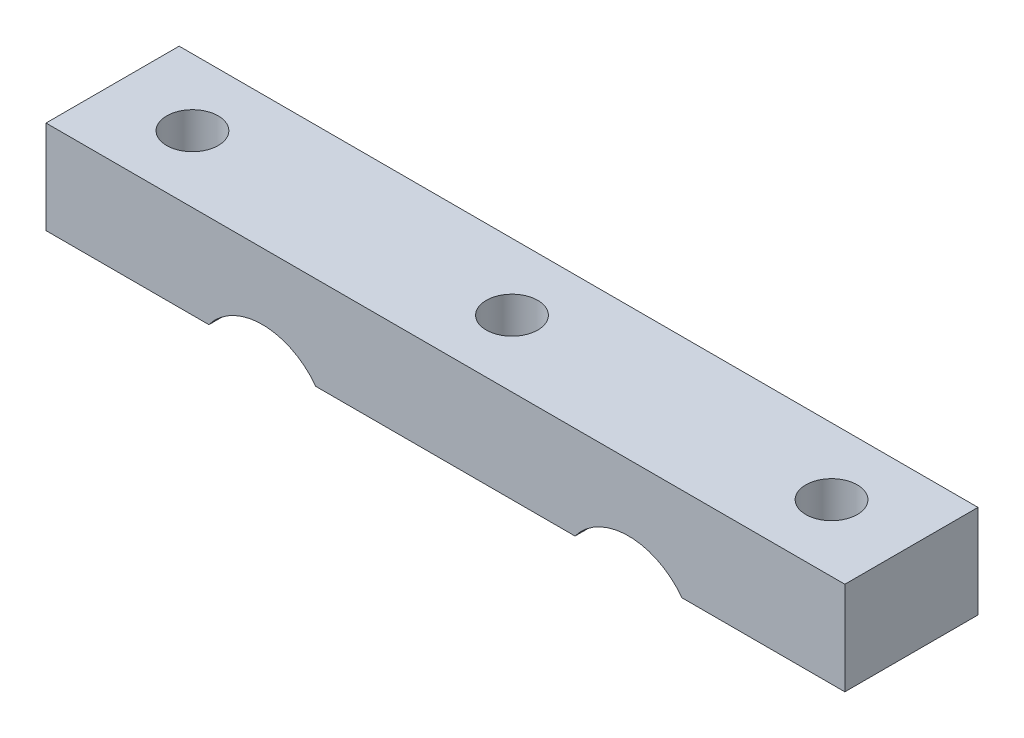
SolidWorks part; units mm, degrees
material "6061-T6 (SS)"
ref_plane "Front Plane" through (0, 0, 0) normal (0, 0, 1) x (1, 0, 0)
ref_plane "Top Plane" through (0, 0, 0) normal (0, 1, 0) x (1, 0, 0)
ref_plane "Right Plane" through (0, 0, 0) normal (1, 0, 0) x (0, 0, -1)
sketch "Sketch1" plane through (0, 0, 0) normal (0, 0, 1) x (1, 0, 0)
  line L0 (-38.1, 17.145) -> (-38.1, 24.7142) construction
  line L3 (-38.1, 17.145) -> (-22.5615, 17.145) construction
  line L5 (38.1, 33.6042) -> (38.1, 24.7142)
  line L6 (22.5615, 24.7142) -> (38.1, 24.7142)
  line L7 (-38.1, 24.7142) -> (-22.5615, 24.7142)
  line L8 (-38.1, 24.7142) -> (-38.1, 33.6042)
  line L9 (-38.1, 33.6042) -> (38.1, 33.6042)
  line L10 (-38.1, 20.9296) -> (38.1, 20.9296) construction
  line L11 (-12.3635, 24.7142) -> (12.3635, 24.7142)
  line L12 (-12.3635, 17.145) -> (12.3635, 17.145) construction
  line L13 (22.5615, 17.145) -> (38.1, 17.145) construction
  arc A0 (-12.3635, 24.7142) -> (-22.5615, 24.7142) centre (-17.4625, 20.9296) ccw
  arc A1 (22.5615, 17.145) -> (12.3635, 17.145) centre (17.4625, 20.9296) cw construction
  arc A2 (-22.5615, 17.145) -> (-12.3635, 17.145) centre (-17.4625, 20.9296) ccw construction
  arc A3 (12.3635, 24.7142) -> (22.5615, 24.7142) centre (17.4625, 20.9296) cw
  point P5 (-22.5615, 24.7142)
  dimension "D5" = 76.2
  dimension "D6" = 34.925
  dimension "D7" = 6.35
  dimension "D8" = 6.35
  dimension "D9" = 38.1
  dimension "D2" = 17.4625
  dimension "D1" = 17.145
  dimension "D3" = 8.89
  dimension "D4" = 7.5692
extrude "Boss-Extrude1" add sketch "Sketch1" along normal blind 12.7
sketch "Sketch3" plane through (0, 33.6042, 0) normal (0, 1, 0) x (1, 0, 0)
  line L0 (38.1, -6.35) -> (-38.1, -6.35) construction
  line L1 (38.1, -12.7) -> (38.1, 0) construction
  line L2 (-38.1, -12.7) -> (-38.1, 0) construction
  point P6 (0, -6.35)
  point P7 (-30.48, -6.35)
  point P8 (30.48, -6.35)
  dimension "D1" = 7.62
  dimension "D2" = 7.62
hole_wizard "#10 (0.1935) Diameter Hole1" positions "3DSketch1" profile "Sketch4" hole size "#10" standard "ANSI Inch" end condition through all
sketch3d "3DSketch1"
  point P0 (-30.48, 33.6042, 6.35)
  point P3 (0, 33.6042, 6.35)
  point P6 (30.48, 33.6042, 6.35)
sketch "Sketch4" plane through (-30.48, 33.6042, 6.35) normal (1, 0, 0) x (0, 0, 1)
  line L0 (0, 0) -> (0, 8.89)
  line L1 (0, 8.89) -> (2.4574, 8.89)
  line L2 (2.4574, 8.89) -> (2.4574, 0)
  line L5 (2.4574, 0) -> (0, 0)
  line L11 (0, -6.35) -> (0, 107.95) construction
  dimension "Thru Hole Dia." = 4.9149
  dimension "Thru Hole Depth" = 8.89
